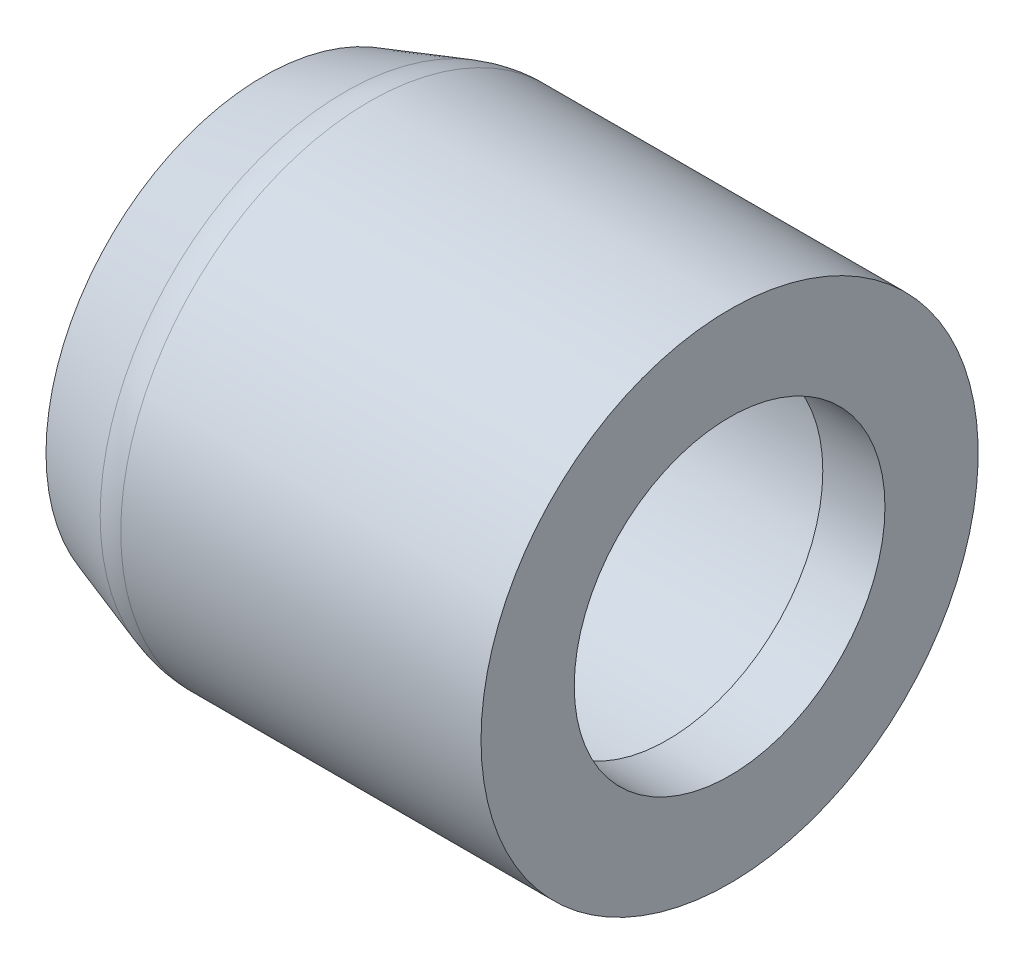
SolidWorks part; units mm, degrees
ref_plane "Alzado" through (0, 0, 0) normal (0, 0, 1) x (1, 0, 0)
ref_plane "Planta" through (0, 0, 0) normal (0, 1, 0) x (1, 0, 0)
ref_plane "Vista lateral" through (0, 0, 0) normal (1, 0, 0) x (0, 0, -1)
sketch "Croquis1" plane through (0, 0, 0) normal (0, 0, 1) x (1, 0, 0)
  line L0 (0, 0) -> (31.9942, 0) construction
  line L1 (0, 12.5) -> (26, 12.5)
  line L2 (26, 12.5) -> (26, 10)
  line L3 (26, 10) -> (30, 10)
  line L4 (30, 10) -> (30, 16)
  line L5 (30, 16) -> (6, 16)
  line L6 (6, 16) -> (0, 14)
  line L7 (0, 12.5) -> (0, 14)
  dimension "D1" = 20
  dimension "D2" = 4
  dimension "D3" = 25
  dimension "D4" = 32
  dimension "D5" = 1.5
  dimension "D6" = 30
  dimension "D7" = 6
revolve "Revolución1" add sketch "Croquis1" angle 360 about L0
fillet "Redondeo1" radius 5 1 edges at (6, 0, 16)
